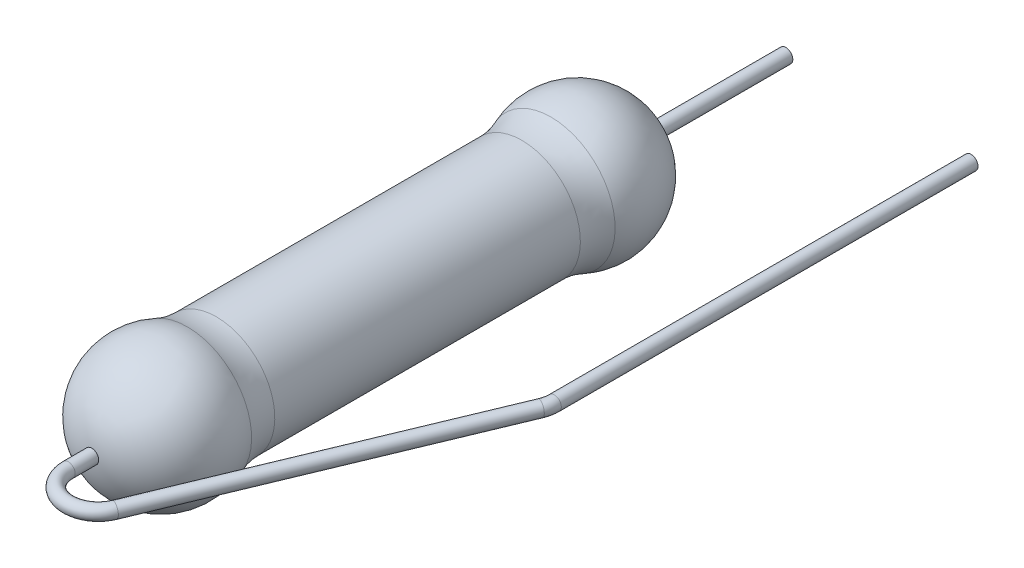
SolidWorks part; units mm, degrees
ref_plane "Front Plane" through (0, 0, 0) normal (0, 0, 1) x (1, 0, 0)
ref_plane "Top Plane" through (0, 0, 0) normal (0, 1, 0) x (1, 0, 0)
ref_plane "Right Plane" through (0, 0, 0) normal (1, 0, 0) x (0, 0, -1)
sketch "Sketch1" plane through (0, 0, 0) normal (0, 0, 1) x (1, 0, 0)
  circle A0 centre (0, 0) radius 0.15
extrude "Boss-Extrude2" add sketch "Sketch1" along normal blind 1 and the other way blind 2
sketch "Sketch4" plane through (0, 0, 0) normal (1, 0, 0) x (0, 0, -1)
  line L0 (-1, 0) -> (-2.5, 0)
  line L1 (-1, 0.15) -> (-1, -0.15) construction
  line L2 (0.165, 0) -> (-0.165, 0) construction
  line L3 (-1, 0.15) -> (-1.0075, 0.15)
  line L4 (-1.0075, 0.15) -> (-1, 0.15)
  line L5 (-1, 0.15) -> (-1, 0)
  line L6 (-2.5, 0) -> (-4, 0)
  line L7 (-1, 0.15) -> (-1, 0)
  line L12 (-4, 0) -> (-11.5, 0)
  line L17 (-11.5, 0) -> (-13, 0)
  line L18 (-10.3001, 1.2613) -> (-3.6999, 1.2613)
  line L19 (-1, 0.15) -> (-1.0075, 0.15)
  line L20 (-13, 0) -> (-13, 0.15)
  line L21 (-12.9925, 0.15) -> (-13, 0.15)
  arc A0 (-1.0075, 0.15) -> (-3.074, 1.3858) centre (-2.5, 0) ccw
  arc A1 (-10.926, 1.3858) -> (-12.9925, 0.15) centre (-11.5, 0) ccw
  arc A2 (-10.926, 1.3858) -> (-10.3001, 1.2613) centre (-10.3001, 2.8969) ccw
  arc A3 (-3.6999, 1.2613) -> (-3.074, 1.3858) centre (-3.6999, 2.8969) ccw
revolve "Revolve2" add sketch "Sketch4" angle 360 about L12
sketch "Sketch5" plane through (0, 0, 13) normal (0, 0, 1) x (1, 0, 0)
  circle A0 centre (0, 0) radius 0.15
extrude "Boss-Extrude3" add sketch "Sketch5" along normal blind 0.5
sketch "Sketch6" plane through (0, 0, 0) normal (0, 0, 1) x (1, 0, 0)
  line L0 (0, 0) -> (4, 0)
  circle A1 centre (0, 0) radius 0.15
  circle A2 centre (4, 0) radius 0.15
extrude "Boss-Extrude4" add sketch "Sketch6" along normal blind 7 and the other way blind 2 separate body
sketch "Sketch7" plane through (0, 0, 0) normal (0, 1, 0) x (1, 0, 0)
  line L0 (4.0888, -7.3069) -> (1.3888, -13.8069)
  line L2 (1.1117, -13.6918) -> (3.8117, -7.1918)
  arc A0 (4.0888, -7.3069) -> (4.15, -7) centre (3.35, -7) ccw
  arc A1 (3.8117, -7.1918) -> (3.85, -7) centre (3.35, -7) ccw
  arc A2 (0.15, -13.5) -> (1.1117, -13.6918) centre (0.65, -13.5) ccw
  arc A3 (-0.15, -13.5) -> (1.3888, -13.8069) centre (0.65, -13.5) ccw
sketch "Sketch16" plane through (0, 0, 7) normal (0, 0, 1) x (1, 0, 0)
  circle A0 centre (4, 0) radius 0.15
sweep "Sweep3" add profiles "Sketch16" path "Sketch7"
